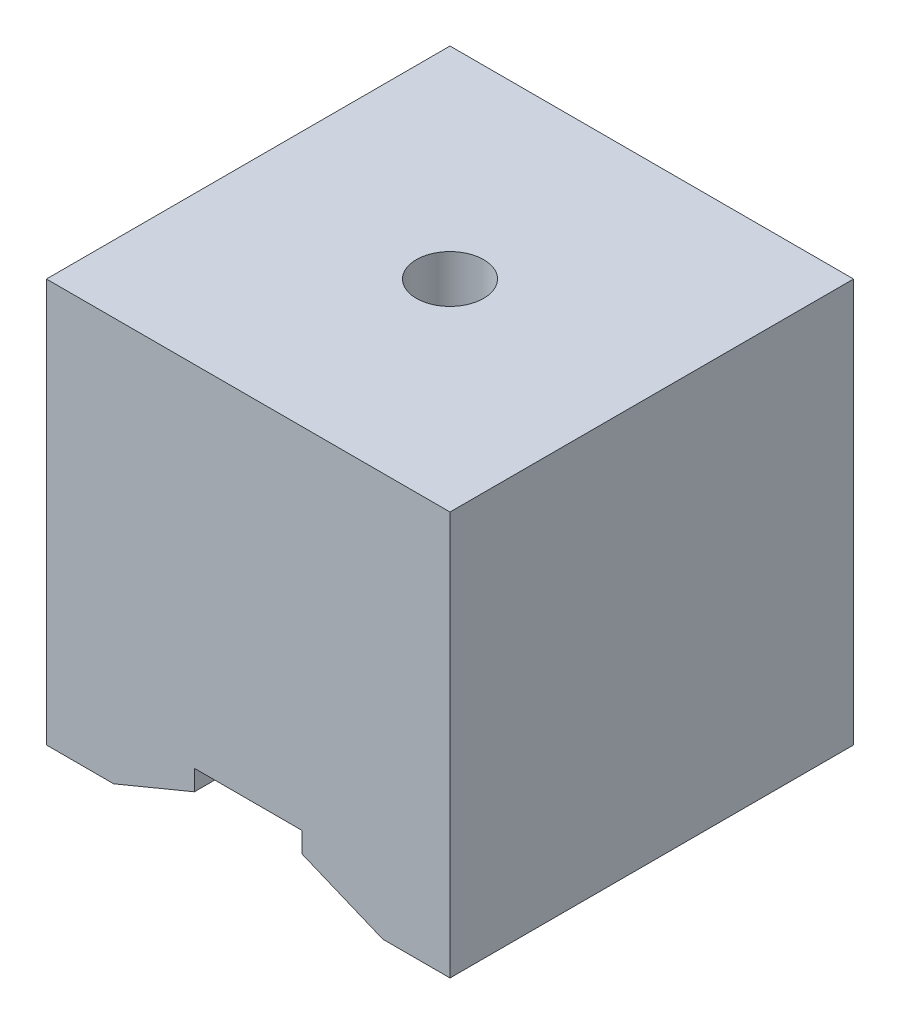
SolidWorks part; units mm, degrees
ref_plane "前视基准面" through (0, 0, 0) normal (0, 0, 1) x (1, 0, 0)
ref_plane "上视基准面" through (0, 0, 0) normal (0, 1, 0) x (1, 0, 0)
ref_plane "右视基准面" through (0, 0, 0) normal (1, 0, 0) x (0, 0, -1)
sketch "草图1" plane through (0, 0, 0) normal (0, 0, 1) x (1, 0, 0)
  line L1 (0, 0) -> (30, 0)
  line L2 (0, 0) -> (0, 30)
  line L3 (0, 30) -> (30, 30)
  line L4 (30, 0) -> (30, 30)
  dimension "D1" = 30
  dimension "D2" = 30
extrude "凸台-拉伸1" add sketch "草图1" along normal blind 30
sketch "草图2" plane through (0, 0, 30) normal (0, 0, 1) x (1, 0, 0)
  line L0 (5, 0) -> (11, 2.4853)
  line L1 (0, 0) -> (30, 0) construction
  line L2 (11, 2.4853) -> (11, 4)
  line L3 (11, 4) -> (19, 4)
  line L4 (19, 4) -> (19, 2.4853)
  line L7 (19, 2.4853) -> (25, 0)
  line L8 (25, 0) -> (5, 0)
  line L10 (15, 30) -> (15, -4.8116) construction
  line L11 (30, 30) -> (0, 30) construction
  dimension "D1" = 20
  dimension "D2" = 8
  dimension "D3" = 135
  dimension "D4" = 4
extrude "切除-拉伸1" cut sketch "草图2" against normal through all
hole_wizard "M6 螺纹孔1" positions "草图4" profile "草图3" tap size "M6" standard "Iso"
sketch "草图4" plane through (0, 30, 0) normal (0, 1, 0) x (1, 0, 0)
  line L0 (15, 0) -> (15, -23.4855) construction
  line L1 (30, 0) -> (0, 0) construction
  line L4 (0, -15) -> (27.0114, -15) construction
  line L5 (0, -30) -> (0, 0) construction
  point P0 (15, -15)
sketch "草图3" plane through (15, 30, 15) normal (1, 0, 0) x (0, 0, 1)
  line L0 (0, 0) -> (0, 16.5022)
  line L1 (0, 16.5022) -> (2.5, 15)
  line L2 (2.5, 15) -> (2.5, 0)
  line L5 (2.5, 0) -> (0, 0)
  line L10 (0, 16.5022) -> (-2.5, 15) construction
  line L11 (0, -6.35) -> (0, 107.95) construction
  dimension "螺纹孔钻头直径" = 5
  dimension "螺纹孔钻头深度" = 15
  dimension "导头角度" = 118
cosmetic thread "孔螺蚊线1" parameters "D1"=12, "D2"=6
